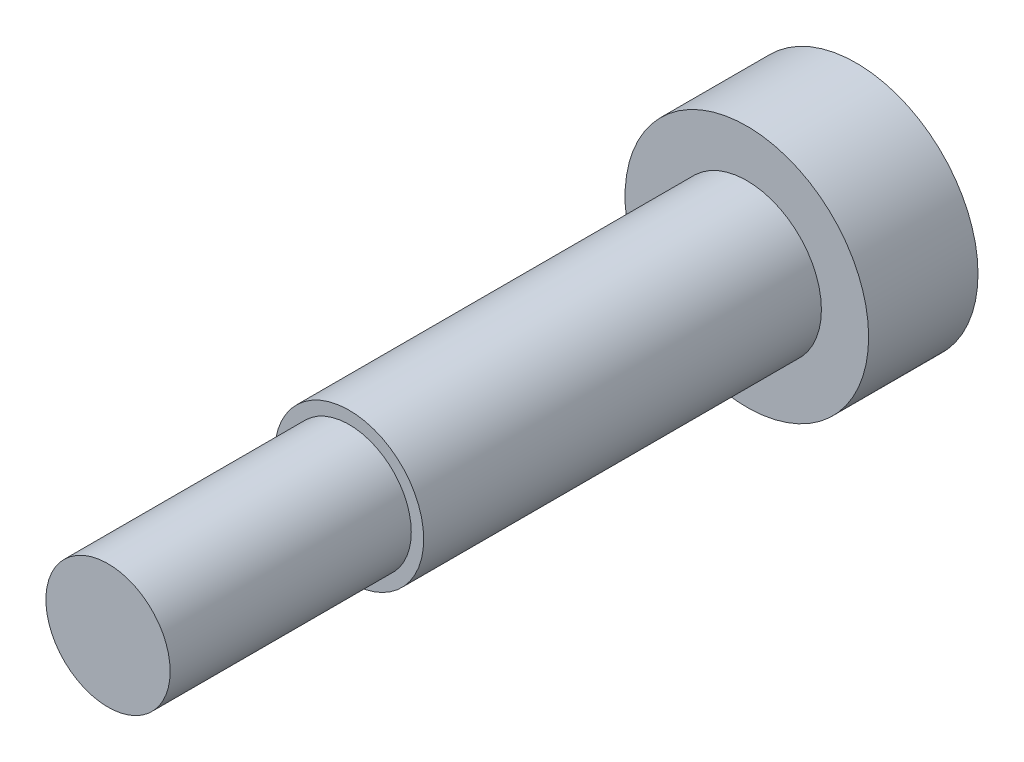
SolidWorks part; units mm, degrees
ref_plane "前视基准面" through (0, 0, 0) normal (0, 0, 1) x (1, 0, 0)
ref_plane "上视基准面" through (0, 0, 0) normal (0, 1, 0) x (1, 0, 0)
ref_plane "右视基准面" through (0, 0, 0) normal (1, 0, 0) x (0, 0, -1)
sketch "草图1" plane through (0, 0, 0) normal (0, 0, 1) x (1, 0, 0)
  circle A0 centre (0, 0) radius 4.9
  dimension "D1" = 9.8
extrude "凸台-拉伸1" add sketch "草图1" along normal blind 4.4
sketch "草图2" plane through (0, 0, 4.4) normal (0, 0, 1) x (1, 0, 0)
  circle A0 centre (0, 0) radius 3
  dimension "D1" = 6
extrude "凸台-拉伸2" add sketch "草图2" along normal blind 16
sketch "草图3" plane through (0, 0, 20.4) normal (0, 0, 1) x (1, 0, 0)
  circle A0 centre (0, 0) radius 2.5
  dimension "D1" = 5
extrude "凸台-拉伸3" add sketch "草图3" along normal blind 9.7
sketch "草图4" plane through (0, 0, 0) normal (0, 0, -1) x (-1, 0, 0)
  line L1 (0, 1.7321) -> (-1.5, 0.866)
  line L2 (-1.5, 0.866) -> (-1.5, -0.866)
  line L3 (-1.5, -0.866) -> (0, -1.7321)
  line L4 (0, -1.7321) -> (1.5, -0.866)
  line L5 (1.5, -0.866) -> (1.5, 0.866)
  line L6 (1.5, 0.866) -> (0, 1.7321)
  circle A0 centre (0, 0) radius 1.5 construction
  dimension "D1" = 3
extrude "切除-拉伸1" cut sketch "草图4" against normal blind 2
